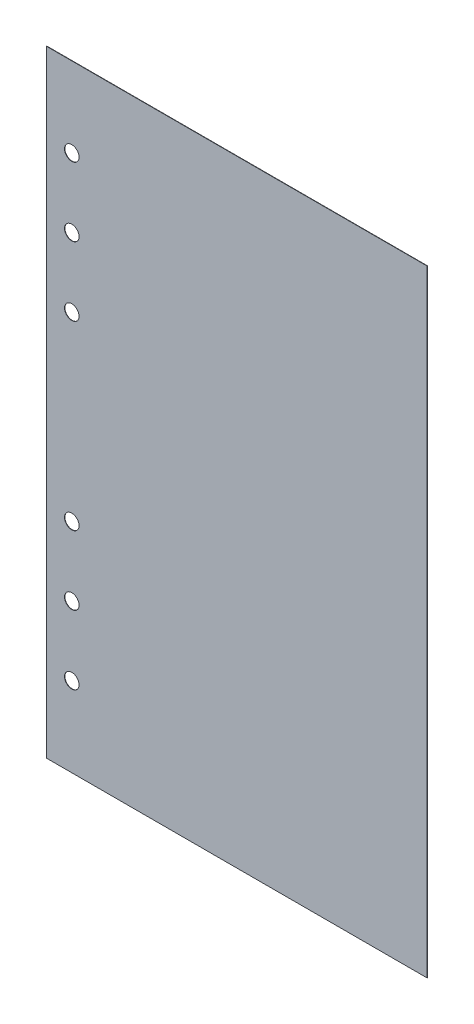
SolidWorks part; units mm, degrees
ref_plane "Спереди" through (0, 0, 0) normal (0, 0, 1) x (1, 0, 0)
ref_plane "Сверху" through (0, 0, 0) normal (0, 1, 0) x (1, 0, 0)
ref_plane "Справа" through (0, 0, 0) normal (1, 0, 0) x (0, 0, -1)
sketch "Эскиз1" plane through (0, 0, 0) normal (0, 0, 1) x (1, 0, 0)
  line L0 (0, 85) -> (105, 85) construction
  line L1 (0, 0) -> (105, 0)
  line L2 (0, 0) -> (0, 170)
  line L3 (0, 170) -> (105, 170)
  line L4 (105, 0) -> (105, 170)
  line L5 (7, 85) -> (7, 110) construction
  line L6 (7, 148) -> (7, 129) construction
  line L7 (7, 129) -> (7, 110) construction
  line L8 (7, 41) -> (7, 60) construction
  line L9 (7, 22) -> (7, 41) construction
  circle A0 centre (7, 110) radius 2
  circle A1 centre (7, 129) radius 2
  circle A2 centre (7, 148) radius 2
  circle A3 centre (7, 22) radius 2
  circle A4 centre (7, 41) radius 2
  circle A5 centre (7, 60) radius 2
  dimension "D3" = 4
  dimension "D4" = 4
  dimension "D5" = 4
  dimension "D6" = 19
  dimension "D7" = 19
  dimension "D8" = 50
  dimension "D1" = 105
  dimension "D2" = 170
  dimension "D9" = 7
extrude "Бобышка-Вытянуть1" add sketch "Эскиз1" along normal blind 0.1
